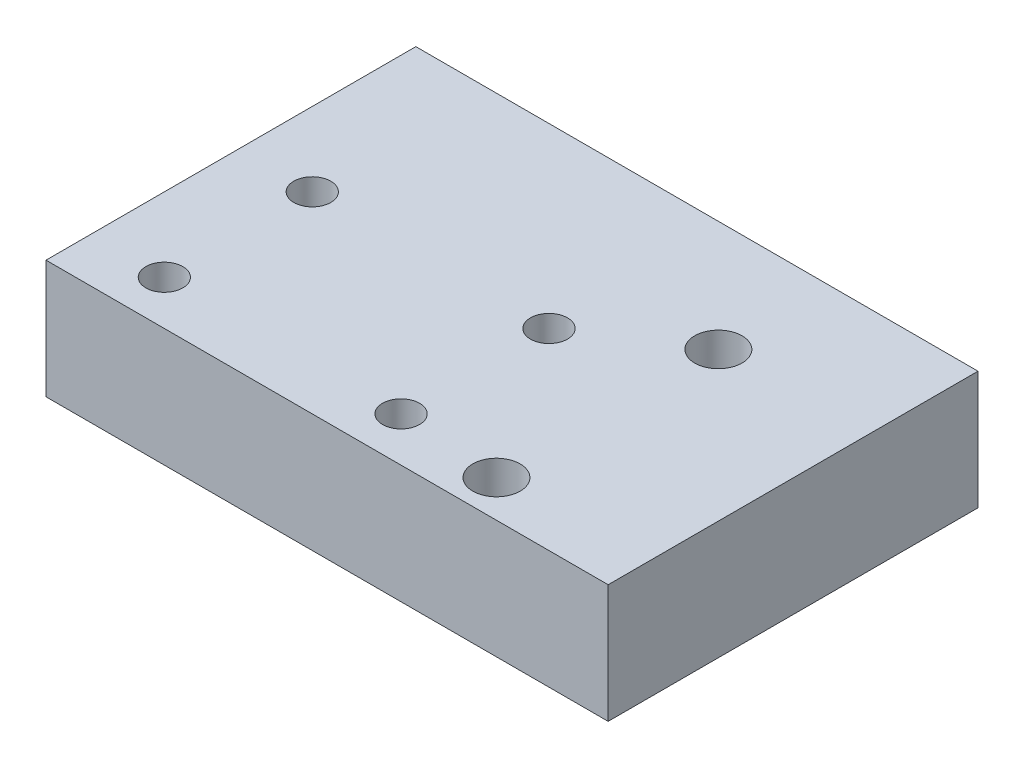
SolidWorks part; units mm, degrees
ref_plane "前视基准面" through (0, 0, 0) normal (0, 0, 1) x (1, 0, 0)
ref_plane "上视基准面" through (0, 0, 0) normal (0, 1, 0) x (1, 0, 0)
ref_plane "右视基准面" through (0, 0, 0) normal (1, 0, 0) x (0, 0, -1)
other "Configuration Table"
sketch "草图1" plane through (0, 0, 0) normal (0, 1, 0) x (1, 0, 0)
  line L1 (-19, -12.5) -> (19, -12.5)
  line L2 (-19, -12.5) -> (-19, 12.5)
  line L3 (-19, 12.5) -> (19, 12.5)
  line L4 (19, -12.5) -> (19, 12.5)
  line L5 (0, 12.5) -> (0, -12.5) construction
  line L6 (-19, 0) -> (19, 0) construction
  point P0 (0, 0)
  dimension "D1" = 25
  dimension "D2" = 38
extrude "凸台-拉伸1" add sketch "草图1" along normal blind 8
sketch "草图2" plane through (0, 0, 0) normal (0, -1, 0) x (1, 0, 0)
  line L0 (2, 12.5) -> (2, -12.5) construction
  line L1 (-19, 12.5) -> (19, 12.5) construction
  line L2 (19, -12.5) -> (-19, -12.5) construction
  line L3 (-1, 15.5) -> (-1, -12.5) construction
  line L4 (-14, 12.5) -> (-14, -12.5) construction
  line L5 (-11, 15.5) -> (-11, -12.5) construction
  circle A0 centre (2, 9.5) radius 1.25
  circle A1 centre (2, -0.5) radius 1.25
  circle A2 centre (-14, 9.5) radius 1.25
  circle A3 centre (-14, -0.5) radius 1.25
  dimension "D2" = 2.5
  dimension "D6" = 2.5
  dimension "D7" = 2.5
  dimension "D1" = 3
  dimension "D3" = 3
  dimension "D4" = 10
  dimension "D5" = 3
extrude "切除-拉伸1" cut sketch "草图2" against normal through all
sketch "草图4" plane through (0, 0, 0) normal (0, -1, 0) x (1, 0, 0)
  line L0 (8.95, -12.5) -> (8.95, 12.5) construction
  line L1 (19, -12.5) -> (-19, -12.5) construction
  line L2 (-19, 12.5) -> (19, 12.5) construction
  line L3 (-19, -12.5) -> (-19, 12.5) construction
  circle A0 centre (8.95, 10) radius 1.6
  circle A1 centre (8.95, -5) radius 1.6
  dimension "D2" = 3.2
  dimension "D1" = 27.95
  dimension "D3" = 15
  dimension "D4" = 2.5
extrude "切除-拉伸2" cut sketch "草图4" against normal through all
